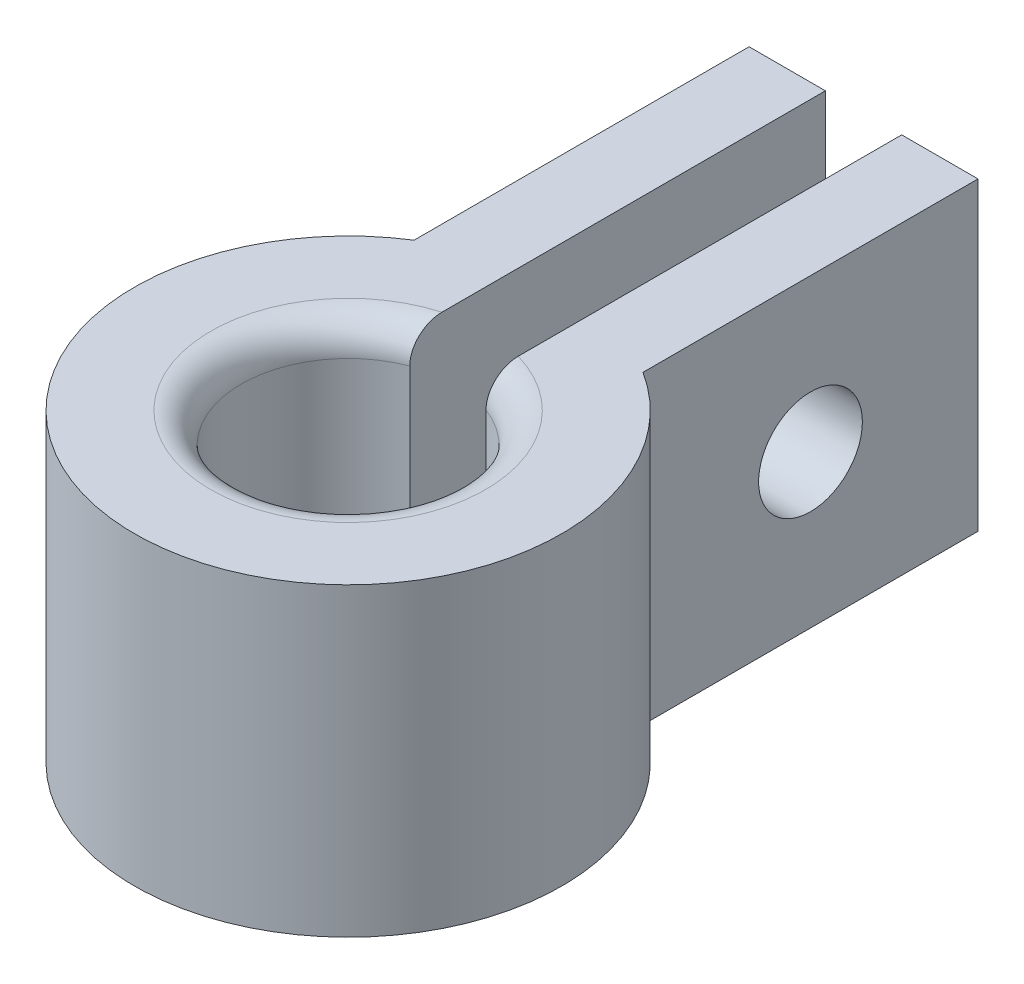
SolidWorks part; units mm, degrees
ref_plane "Front Plane" through (0, 0, 0) normal (0, 0, 1) x (1, 0, 0)
ref_plane "Top Plane" through (0, 0, 0) normal (0, 1, 0) x (1, 0, 0)
ref_plane "Right Plane" through (0, 0, 0) normal (1, 0, 0) x (0, 0, -1)
sketch "Sketch1" plane through (0, 0, 0) normal (0, 1, 0) x (1, 0, 0)
  line L0 (0, 116.7614) -> (0, -100.8523) construction
  line L1 (13.75, 3.2692) -> (13.75, 16.8875)
  line L2 (18.75, 16.8875) -> (18.75, 5.9108)
  line L3 (15, 0) -> (15, 17.0653) construction
  line L4 (13.75, 16.8875) -> (11.25, 16.8875)
  line L5 (11.25, 16.8875) -> (11.25, 5.9108)
  line L6 (16.25, 16.8875) -> (18.75, 16.8875)
  line L7 (16.25, 3.2692) -> (16.25, 16.8875)
  arc A0 (11.25, 5.9108) -> (18.75, 5.9108) centre (15, 0) ccw
  arc A1 (13.75, 3.2692) -> (16.25, 3.2692) centre (15, 0) ccw
  point P12 (13.75, 6.8875)
  point P13 (16.25, 6.8875)
  dimension "D2" = 7
  dimension "D3" = 7
  dimension "D5" = 2.5
  dimension "D7" = 10.9767
  dimension "D1" = 30
  dimension "D4" = 10
  dimension "D6" = 2.5
extrude "Boss-Extrude1" add sketch "Sketch1" along normal blind 10
sketch "Sketch2" plane through (18.75, 0, 0) normal (1, 0, 0) x (0, 0, -1)
  line L0 (11.3991, 10) -> (11.3991, 0) construction
  line L1 (5.9108, 10) -> (16.8875, 10) construction
  line L2 (5.9108, 0) -> (16.8875, 0) construction
  line L3 (11.3991, 5) -> (16.8875, 5) construction
  line L6 (16.8875, 10) -> (16.8875, 0) construction
  circle A0 centre (11.3991, 5) radius 1.7
  dimension "D1" = 3.4
extrude "Cut-Extrude1" cut sketch "Sketch2" against normal up to surface (7.5 mm away) up to face at (11.25, 5, -11.3991)
fillet "Fillet1" radius 1 1 edges at (15, 10, 3.5)
